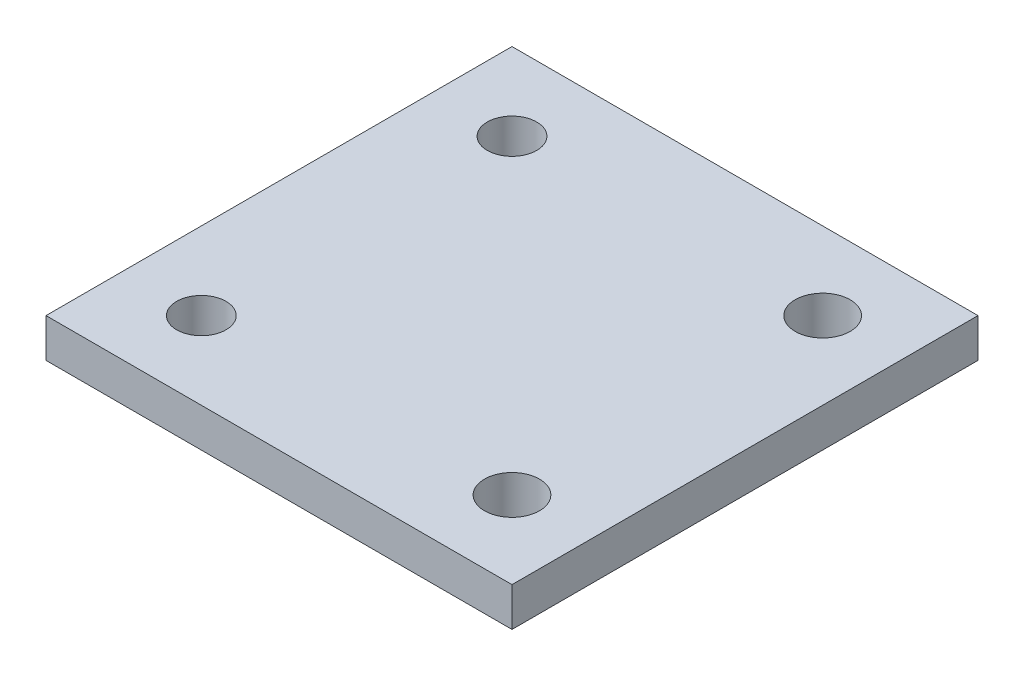
SolidWorks part; units mm, degrees
ref_plane "Front Plane" through (0, 0, 0) normal (0, 0, 1) x (1, 0, 0)
ref_plane "Top Plane" through (0, 0, 0) normal (0, 1, 0) x (1, 0, 0)
ref_plane "Right Plane" through (0, 0, 0) normal (1, 0, 0) x (0, 0, -1)
sketch "Sketch1" plane through (0, 0, 0) normal (0, 1, 0) x (1, 0, 0)
  line L0 (0, -55) -> (0, 55) construction
  line L1 (-19.05, -19.05) -> (19.05, -19.05)
  line L2 (-19.05, -19.05) -> (-19.05, 19.05)
  line L3 (-19.05, 19.05) -> (19.05, 19.05)
  line L4 (19.05, -19.05) -> (19.05, 19.05)
  line L5 (-19.05, -19.05) -> (19.05, 19.05) construction
  line L6 (-19.05, 19.05) -> (19.05, -19.05) construction
  point P0 (0, 0)
  dimension "D1" = 38.1
  dimension "D2" = 38.1
extrude "Boss-Extrude1" add sketch "Sketch1" along normal mid plane 3.175
sketch "Sketch2" plane through (0, 1.5875, 0) normal (0, 1, 0) x (1, 0, 0)
  line L0 (-12.7, 12.7) -> (-12.7, -12.7) construction
  line L1 (-1.7463, 0) -> (1.7463, 0) construction
  line L2 (-12.7, 12.7) -> (12.7, 12.7) construction
  line L3 (0, -1.7463) -> (0, 1.7463) construction
  point P0 (12.7, 12.7)
  point P1 (12.7, -12.7)
  point P2 (-12.7, 12.7)
  point P3 (-12.7, -12.7)
  point P8 (-12.7, 0)
  point P13 (0, 12.7)
  dimension "D1" = 25.4
  dimension "D2" = 25.4
hole_wizard "#10-32 Tapped Hole1" positions "Sketch3" profile "Sketch5" tap size "#10-32" standard "ANSI Inch" end condition through all
sketch "Sketch3" plane through (0, 1.5875, 0) normal (0, 1, 0) x (1, 0, 0)
  point P0 (-12.7, 12.7)
  point P3 (-12.7, -12.7)
cosmetic thread "Hole Thread1"
cosmetic thread "Hole Thread2"
sketch "Sketch5" plane through (-12.7, 1.5875, -12.7) normal (1, 0, 0) x (0, 0, 1)
  line L0 (0, 0) -> (0, 3.175)
  line L1 (0, 3.175) -> (2.0193, 3.175)
  line L2 (2.0193, 3.175) -> (2.0193, 0)
  line L5 (2.0193, 0) -> (0, 0)
  line L11 (0, -6.35) -> (0, 107.95) construction
  dimension "Thru Tap Drill Dia." = 4.0386
  dimension "Thru Tap Drill Depth" = 3.175
hole_wizard "#8 Clearance Hole1" positions "Sketch6" profile "Sketch8" hole size "#8" standard "ANSI Inch" end condition through all
sketch "Sketch6" plane through (0, 1.5875, 0) normal (0, 1, 0) x (1, 0, 0)
  point P0 (12.7, 12.7)
  point P6 (12.7, -12.7)
sketch "Sketch8" plane through (12.7, 1.5875, -12.7) normal (1, 0, 0) x (0, 0, 1)
  line L0 (0, 0) -> (0, 3.175)
  line L1 (0, 3.175) -> (2.2479, 3.175)
  line L2 (2.2479, 3.175) -> (2.2479, 0)
  line L5 (2.2479, 0) -> (0, 0)
  line L11 (0, -6.35) -> (0, 107.95) construction
  dimension "Thru Hole Dia." = 4.4958
  dimension "Thru Hole Depth" = 3.175
